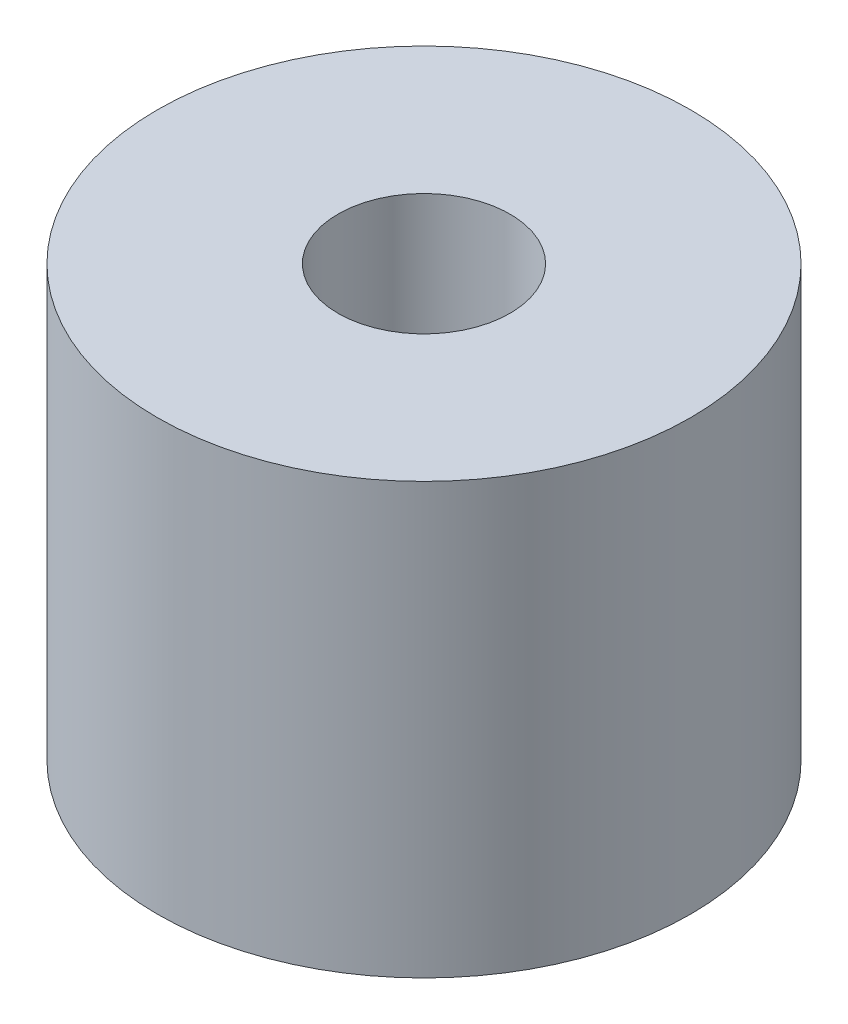
SolidWorks part; units mm, degrees
ref_plane "Front" through (0, 0, 0) normal (0, 0, 1) x (1, 0, 0)
ref_plane "Top" through (0, 0, 0) normal (0, 1, 0) x (1, 0, 0)
ref_plane "Side" through (0, 0, 0) normal (1, 0, 0) x (0, 0, -1)
sketch "Sketch1" plane through (0, 0, 0) normal (0, 1, 0) x (1, 0, 0)
  circle A0 centre (0, 0) radius 15.5
  dimension "D1" = 31
extrude "Boss-Extrude1" add sketch "Sketch1" along normal mid plane 25 contours A0
hole_wizard "Ø10.0mm Dowel Hole2" positions "Sketch5" profile "Sketch6" hole size "Ø10.0" standard "ANSI Metric" end condition through all
sketch "Sketch5" plane through (0, 12.5, 0) normal (0, 1, 0) x (1, 0, 0)
  point P0 (0, 0)
sketch "Sketch6" plane through (0, 12.5, 0) normal (1, 0, 0) x (0, 0, 1)
  line L0 (0, 0) -> (0, 25)
  line L1 (0, 25) -> (5, 25)
  line L2 (5, 25) -> (5, 0)
  line L5 (5, 0) -> (0, 0)
  line L11 (0, -6.35) -> (0, 107.95) construction
  dimension "Thru Hole Dia." = 10
  dimension "Thru Hole Depth" = 25
